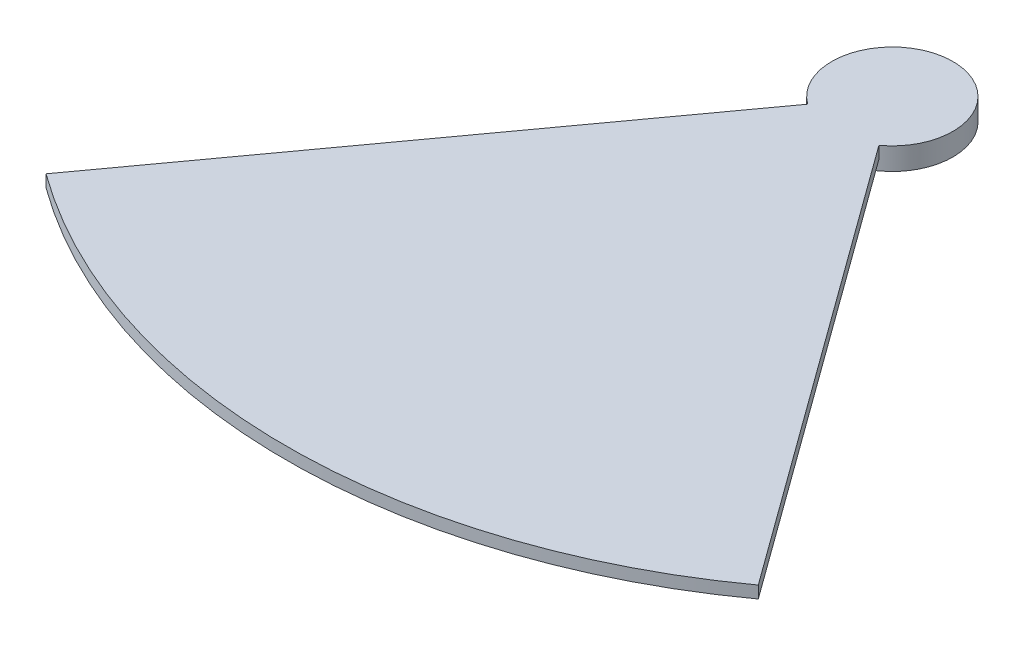
SolidWorks part; units mm, degrees
ref_plane "Front Plane" through (0, 0, 0) normal (0, 0, 1) x (1, 0, 0)
ref_plane "Top Plane" through (0, 0, 0) normal (0, 1, 0) x (1, 0, 0)
ref_plane "Right Plane" through (0, 0, 0) normal (1, 0, 0) x (0, 0, -1)
sketch "Sketch1" plane through (0, 0, 0) normal (0, 1, 0) x (1, 0, 0)
  circle A0 centre (0, 0) radius 3.175
  circle A1 centre (0, 0) radius 6
  dimension "D1" = 6.35
  dimension "D2" = 12
extrude "Boss-Extrude1" add sketch "Sketch1" along normal blind 16
sketch "Sketch2" plane through (0, 16, 0) normal (0, 1, 0) x (1, 0, 0)
  circle A0 centre (0, 0) radius 30
  dimension "D1" = 60
extrude "Boss-Extrude2" add sketch "Sketch2" along normal blind 5
sketch "Sketch3" plane through (0, 21, 0) normal (0, 1, 0) x (1, 0, 0)
  line L2 (17.6336, -24.2705) -> (176.3356, -242.7051)
  line L3 (-17.6336, -24.2705) -> (-176.3356, -242.7051)
  arc A0 (17.6336, -24.2705) -> (-17.6336, -24.2705) centre (0, 0) ccw
  arc A1 (-176.3356, -242.7051) -> (176.3356, -242.7051) centre (0, 0) ccw
  dimension "D1" = 60
  dimension "D2" = 600
extrude "Boss-Extrude3" add sketch "Sketch3" along normal blind 6
